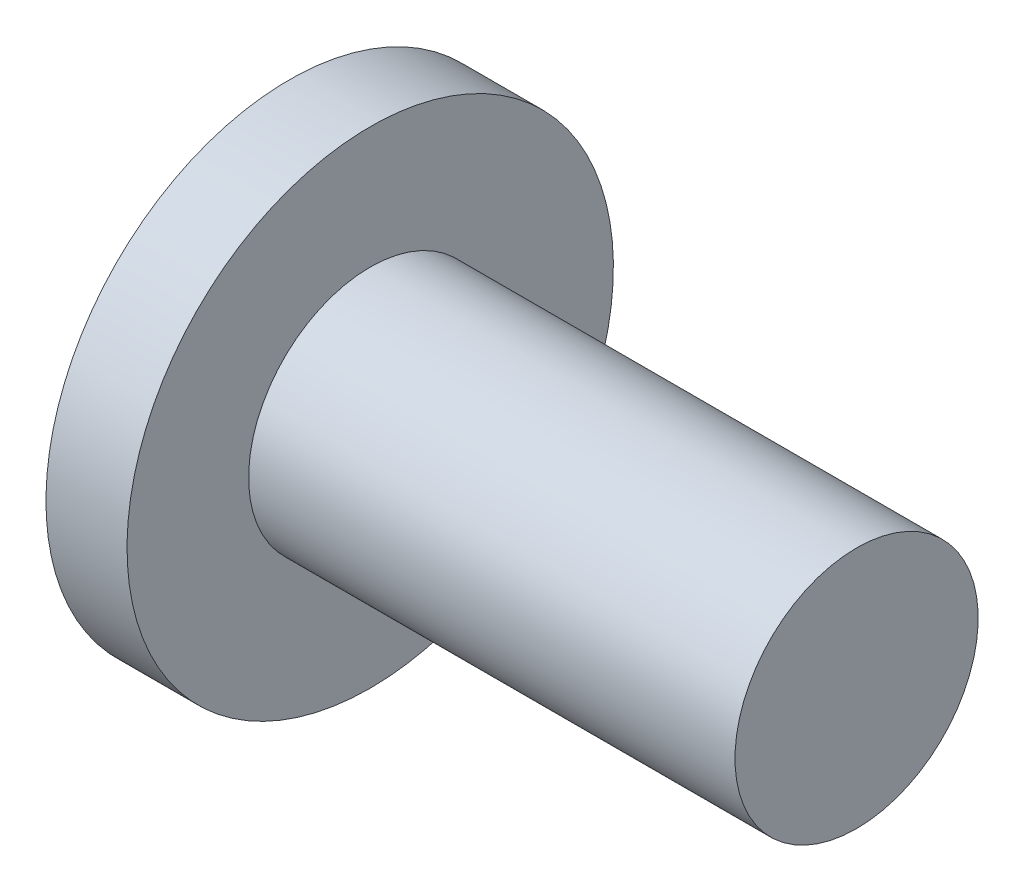
SolidWorks part; units mm, degrees
ref_plane "前视基准面" through (0, 0, 0) normal (0, 0, 1) x (1, 0, 0)
ref_plane "上视基准面" through (0, 0, 0) normal (0, 1, 0) x (1, 0, 0)
ref_plane "右视基准面" through (0, 0, 0) normal (1, 0, 0) x (0, 0, -1)
other "Configuration Table"
sketch "草图1" plane through (0, 0, 0) normal (0, 0, 1) x (1, 0, 0)
  line L0 (0, 0) -> (6, 0)
  line L1 (0, 0) -> (0, 1.5)
  line L2 (0, 1.5) -> (-1, 1.5)
  line L3 (6, 0) -> (6, -1.5)
  line L4 (6, -1.5) -> (4.7823, -1.5) construction
  line L5 (-1, 1.5) -> (-1, -1.5)
  line L6 (-1, -1.5) -> (6, -1.5)
  dimension "D1" = 6
  dimension "D2" = 1.5
  dimension "D3" = 1
  dimension "D4" = 1.5
revolve "旋转1" add sketch "草图1" angle 360 about L6
